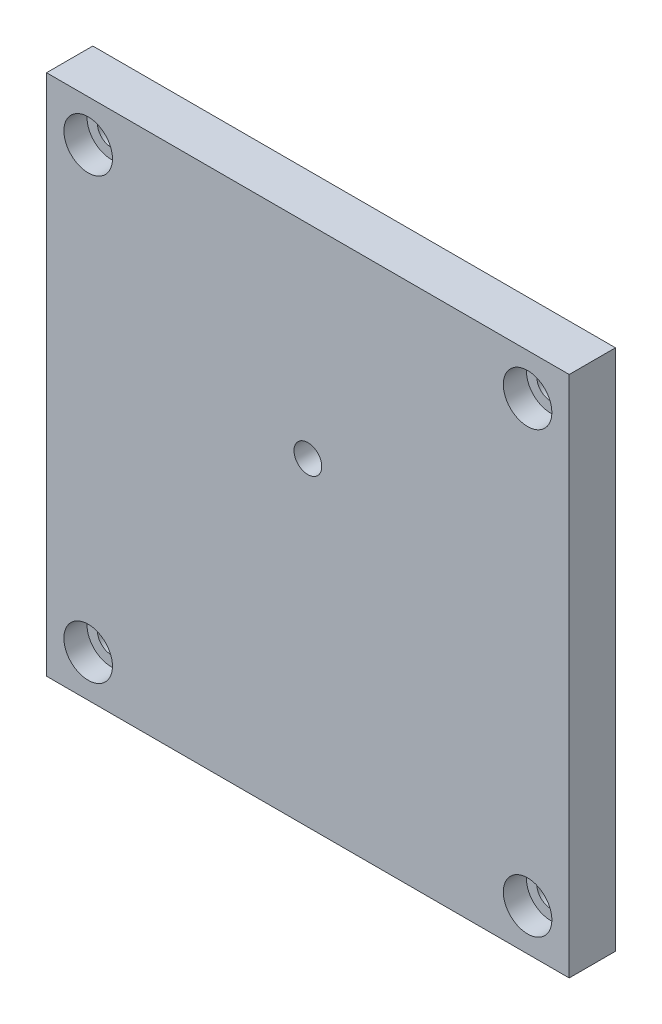
SolidWorks part; units mm, degrees
ref_plane "Front Plane" through (0, 0, 0) normal (0, 0, 1) x (1, 0, 0)
ref_plane "Top Plane" through (0, 0, 0) normal (0, 1, 0) x (1, 0, 0)
ref_plane "Right Plane" through (0, 0, 0) normal (1, 0, 0) x (0, 0, -1)
sketch "Sketch1" plane through (0, 0, 0) normal (0, 0, 1) x (1, 0, 0)
  line L0 (-29.21, -29.21) -> (-29.21, 29.21) construction
  line L1 (-28.702, -28.702) -> (28.702, -28.702)
  line L2 (-28.702, -28.702) -> (-28.702, 28.702)
  line L3 (-28.702, 28.702) -> (28.702, 28.702)
  line L4 (28.702, -28.702) -> (28.702, 28.702)
  line L5 (-29.21, 29.21) -> (29.21, 29.21) construction
  line L6 (29.21, 29.21) -> (29.21, -29.21) construction
  line L7 (29.21, -29.21) -> (-29.21, -29.21) construction
  circle A0 centre (-24.13, 24.13) radius 1.524
  circle A1 centre (-24.13, -24.13) radius 1.524
  circle A2 centre (24.13, -24.13) radius 1.524
  circle A3 centre (24.13, 24.13) radius 1.524
  dimension "D5" = 3.048
  dimension "D1" = 0.508
  dimension "D2" = 0.508
  dimension "D3" = 0.508
  dimension "D4" = 0.508
extrude "Boss-Extrude1" add sketch "Sketch1" along normal up to surface (5.08 mm away)
sketch "Sketch2" plane through (0, 0, 5.08) normal (0, 0, 1) x (1, 0, 0)
  circle A0 centre (-24.13, -24.13) radius 2.667
  circle A1 centre (-24.13, 24.13) radius 2.667
  circle A2 centre (24.13, 24.13) radius 2.667
  circle A3 centre (24.13, -24.13) radius 2.667
  dimension "D1" = 5.334
extrude "Cut-Extrude1" cut sketch "Sketch2" against normal blind 2.54
sketch "Sketch3" plane through (0, 0, 5.08) normal (0, 0, 1) x (1, 0, 0)
  circle A0 centre (0, 6.35) radius 1.524
  point P2 (2.87, 5.6644)
  dimension "D1" = 3.048
  dimension "D2" = 6.35
extrude "Cut-Extrude2" cut sketch "Sketch3" against normal through all
